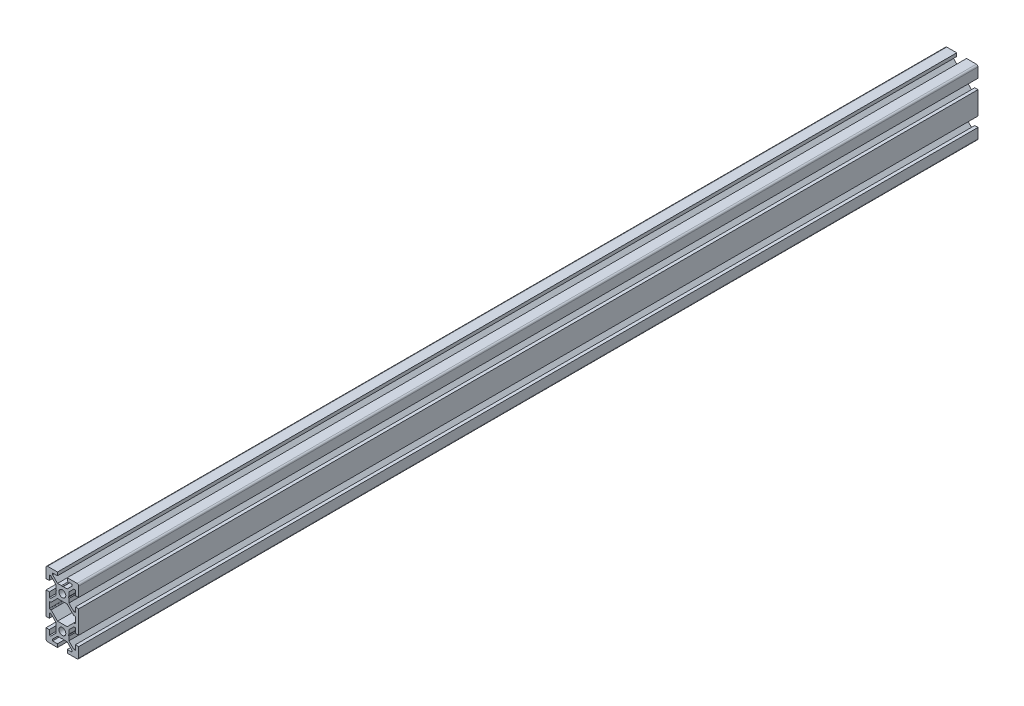
SolidWorks part; units mm, degrees
material "6061 Alloy"
ref_plane "Front Plane" through (0, 0, 0) normal (0, 0, 1) x (1, 0, 0)
ref_plane "Top Plane" through (0, 0, 0) normal (0, 1, 0) x (1, 0, 0)
ref_plane "Right Plane" through (0, 0, 0) normal (1, 0, 0) x (0, 0, -1)
ref_plane "Plane1" through (0, 0, 0) normal (0, 0, 1) x (1, 0, 0)
sketch "Sketch1" plane through (0, 0, 0) normal (0, 0, 1) x (1, 0, 0)
  line L0 (-10, -7) -> (-8, -7)
  line L1 (-8, -7) -> (-8, -4)
  line L2 (-8, -4) -> (-7.0607, -4)
  line L3 (-7.0607, -4) -> (-4, -7.0607)
  line L4 (-4, -7.0607) -> (-4, -9.4804)
  line L5 (-4, -9.4804) -> (-3.7, -10)
  line L6 (-3.7, -10) -> (-4, -10.5196)
  line L7 (-4, -10.5196) -> (-4, -12.9393)
  line L8 (-4, -12.9393) -> (-7.0607, -16)
  line L9 (-7.0607, -16) -> (-8, -16)
  line L10 (-8, -16) -> (-8, -13)
  line L11 (-8, -13) -> (-10, -13)
  line L12 (-10, -13) -> (-10, -19)
  line L13 (-9, -20) -> (-3, -20)
  line L14 (-3, -20) -> (-3, -18)
  line L15 (-3, -18) -> (-6, -18)
  line L16 (-6, -18) -> (-6, -17.0607)
  line L17 (-6, -17.0607) -> (-2.9393, -14)
  line L18 (-2.9393, -14) -> (-0.5196, -14)
  line L19 (-0.5196, -14) -> (0, -13.7)
  line L20 (0, -13.7) -> (0.5196, -14)
  line L21 (0.5196, -14) -> (2.9393, -14)
  line L22 (2.9393, -14) -> (6, -17.0607)
  line L23 (6, -17.0607) -> (6, -18)
  line L24 (6, -18) -> (3, -18)
  line L25 (3, -18) -> (3, -20)
  line L26 (3, -20) -> (9, -20)
  line L27 (10, -19) -> (10, -13)
  line L28 (10, -13) -> (8, -13)
  line L29 (8, -13) -> (8, -16)
  line L30 (8, -16) -> (7.0607, -16)
  line L31 (7.0607, -16) -> (4, -12.9393)
  line L32 (4, -12.9393) -> (4, -10.5196)
  line L33 (4, -10.5196) -> (3.7, -10)
  line L34 (3.7, -10) -> (4, -9.4804)
  line L35 (4, -9.4804) -> (4, -7.0607)
  line L36 (4, -7.0607) -> (7.0607, -4)
  line L37 (7.0607, -4) -> (8, -4)
  line L38 (8, -4) -> (8, -7)
  line L39 (8, -7) -> (10, -7)
  line L40 (10, -7) -> (10, 7)
  line L41 (10, 7) -> (8, 7)
  line L42 (8, 7) -> (8, 4)
  line L43 (8, 4) -> (7.0607, 4)
  line L44 (7.0607, 4) -> (4, 7.0607)
  line L45 (4, 7.0607) -> (4, 9.4804)
  line L46 (4, 9.4804) -> (3.7, 10)
  line L47 (3.7, 10) -> (4, 10.5196)
  line L48 (4, 10.5196) -> (4, 12.9393)
  line L49 (4, 12.9393) -> (7.0607, 16)
  line L50 (7.0607, 16) -> (8, 16)
  line L51 (8, 16) -> (8, 13)
  line L52 (8, 13) -> (10, 13)
  line L53 (10, 13) -> (10, 19)
  line L54 (9, 20) -> (3, 20)
  line L55 (3, 20) -> (3, 18)
  line L56 (3, 18) -> (6, 18)
  line L57 (6, 18) -> (6, 17.0607)
  line L58 (6, 17.0607) -> (2.9393, 14)
  line L59 (2.9393, 14) -> (0.5196, 14)
  line L60 (0.5196, 14) -> (0, 13.7)
  line L61 (0, 13.7) -> (-0.5196, 14)
  line L62 (-0.5196, 14) -> (-2.9393, 14)
  line L63 (-2.9393, 14) -> (-6, 17.0607)
  line L64 (-6, 17.0607) -> (-6, 18)
  line L65 (-6, 18) -> (-3, 18)
  line L66 (-3, 18) -> (-3, 20)
  line L67 (-3, 20) -> (-9, 20)
  line L68 (-10, 19) -> (-10, 13)
  line L69 (-10, 13) -> (-8, 13)
  line L70 (-8, 13) -> (-8, 16)
  line L71 (-8, 16) -> (-7.0607, 16)
  line L72 (-7.0607, 16) -> (-4, 12.9393)
  line L73 (-4, 12.9393) -> (-4, 10.5196)
  line L74 (-4, 10.5196) -> (-3.7, 10)
  line L75 (-3.7, 10) -> (-4, 9.4804)
  line L76 (-4, 9.4804) -> (-4, 7.0607)
  line L77 (-4, 7.0607) -> (-7.0607, 4)
  line L78 (-7.0607, 4) -> (-8, 4)
  line L79 (-8, 4) -> (-8, 7)
  line L80 (-8, 7) -> (-10, 7)
  line L81 (-10, 7) -> (-10, -7)
  line L82 (-8, 1.7) -> (-8, -1.7)
  line L83 (-7.7, -2) -> (-7.0636, -2)
  line L84 (-6.8515, -2.0879) -> (-2.9393, -6)
  line L85 (-2.9393, -6) -> (2.9393, -6)
  line L86 (2.9393, -6) -> (6.8515, -2.0879)
  line L87 (7.0636, -2) -> (7.7, -2)
  line L88 (8, -1.7) -> (8, 1.7)
  line L89 (7.7, 2) -> (7.0636, 2)
  line L90 (6.8515, 2.0879) -> (2.9393, 6)
  line L91 (2.9393, 6) -> (-2.9393, 6)
  line L92 (-2.9393, 6) -> (-6.8515, 2.0879)
  line L93 (-7.0636, 2) -> (-7.7, 2)
  arc A0 (-10, -19) -> (-9, -20) centre (-9, -19) ccw
  arc A1 (9, -20) -> (10, -19) centre (9, -19) ccw
  arc A2 (10, 19) -> (9, 20) centre (9, 19) ccw
  arc A3 (-9, 20) -> (-10, 19) centre (-9, 19) ccw
  arc A4 (-8, -1.7) -> (-7.7, -2) centre (-7.7, -1.7) ccw
  arc A5 (-7.0636, -2) -> (-6.8515, -2.0879) centre (-7.0636, -2.3) cw
  arc A6 (6.8515, -2.0879) -> (7.0636, -2) centre (7.0636, -2.3) cw
  arc A7 (7.7, -2) -> (8, -1.7) centre (7.7, -1.7) ccw
  arc A8 (8, 1.7) -> (7.7, 2) centre (7.7, 1.7) ccw
  arc A9 (7.0636, 2) -> (6.8515, 2.0879) centre (7.0636, 2.3) cw
  arc A10 (-6.8515, 2.0879) -> (-7.0636, 2) centre (-7.0636, 2.3) cw
  arc A11 (-7.7, 2) -> (-8, 1.7) centre (-7.7, 1.7) ccw
extrude "Boss-Extrude1" add sketch "Sketch1" against normal blind 550
ref_plane "Plane2" through (0, 0, 0) normal (1, 0, 0) x (0, 0, -1)
sketch "Sketch2" plane through (0, 0, 0) normal (1, 0, 0) x (0, 0, -1)
  line L0 (0, 10) -> (0, 12.1)
  line L1 (0, 12.1) -> (550, 12.1)
  line L2 (550, 12.1) -> (550, 10)
  line L3 (550, 10) -> (0, 10)
  line L4 (550, 10) -> (0, 10) construction
revolve "Cut-Revolve1" cut sketch "Sketch2" angle 360 about L4
ref_plane "Plane3" through (0, 0, 0) normal (1, 0, 0) x (0, 0, -1)
sketch "Sketch3" plane through (0, 0, 0) normal (1, 0, 0) x (0, 0, -1)
  line L0 (0, -10) -> (0, -7.9)
  line L1 (0, -7.9) -> (550, -7.9)
  line L2 (550, -7.9) -> (550, -10)
  line L3 (550, -10) -> (0, -10)
  line L4 (550, -10) -> (0, -10) construction
revolve "Cut-Revolve2" cut sketch "Sketch3" angle 360 about L4
